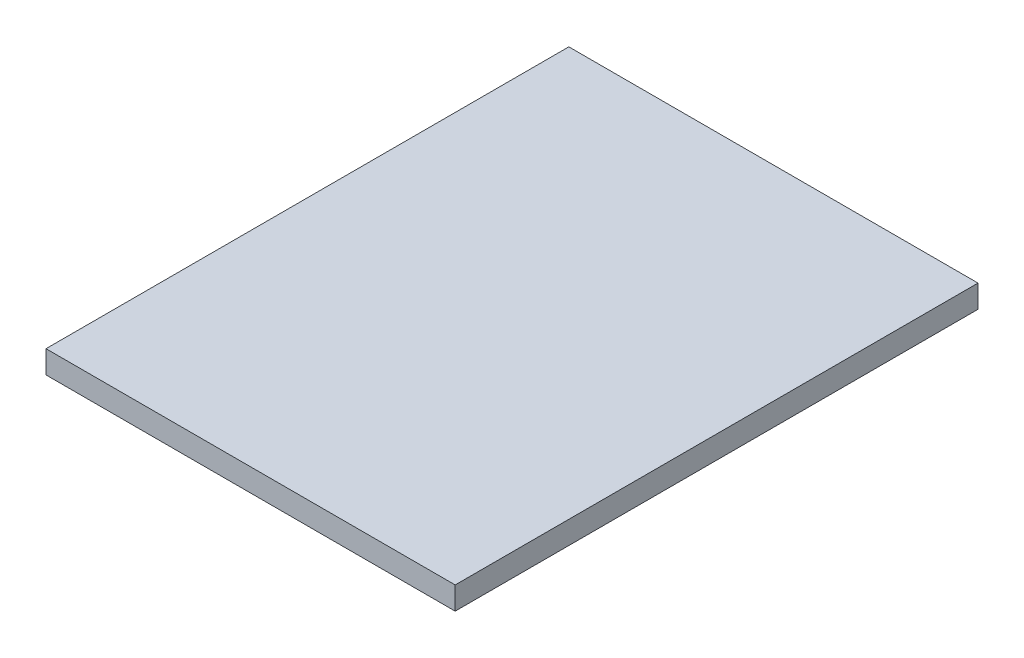
SolidWorks part; units mm, degrees
ref_plane "前基準面" through (0, 0, 0) normal (0, 0, 1) x (1, 0, 0)
ref_plane "上基準面" through (0, 0, 0) normal (0, 1, 0) x (1, 0, 0)
ref_plane "右基準面" through (0, 0, 0) normal (1, 0, 0) x (0, 0, -1)
sketch "草圖1" plane through (0, 0, 0) normal (0, 1, 0) x (1, 0, 0)
  line L1 (-9, 11.5) -> (9, 11.5)
  line L2 (-9, 11.5) -> (-9, -11.5)
  line L3 (-9, -11.5) -> (9, -11.5)
  line L4 (9, 11.5) -> (9, -11.5)
  line L5 (-9, 11.5) -> (9, -11.5) construction
  line L6 (-9, -11.5) -> (9, 11.5) construction
  point P0 (0, 0)
  dimension "D1" = 23
  dimension "D2" = 18
extrude "填料-伸長1" add sketch "草圖1" along normal blind 1
